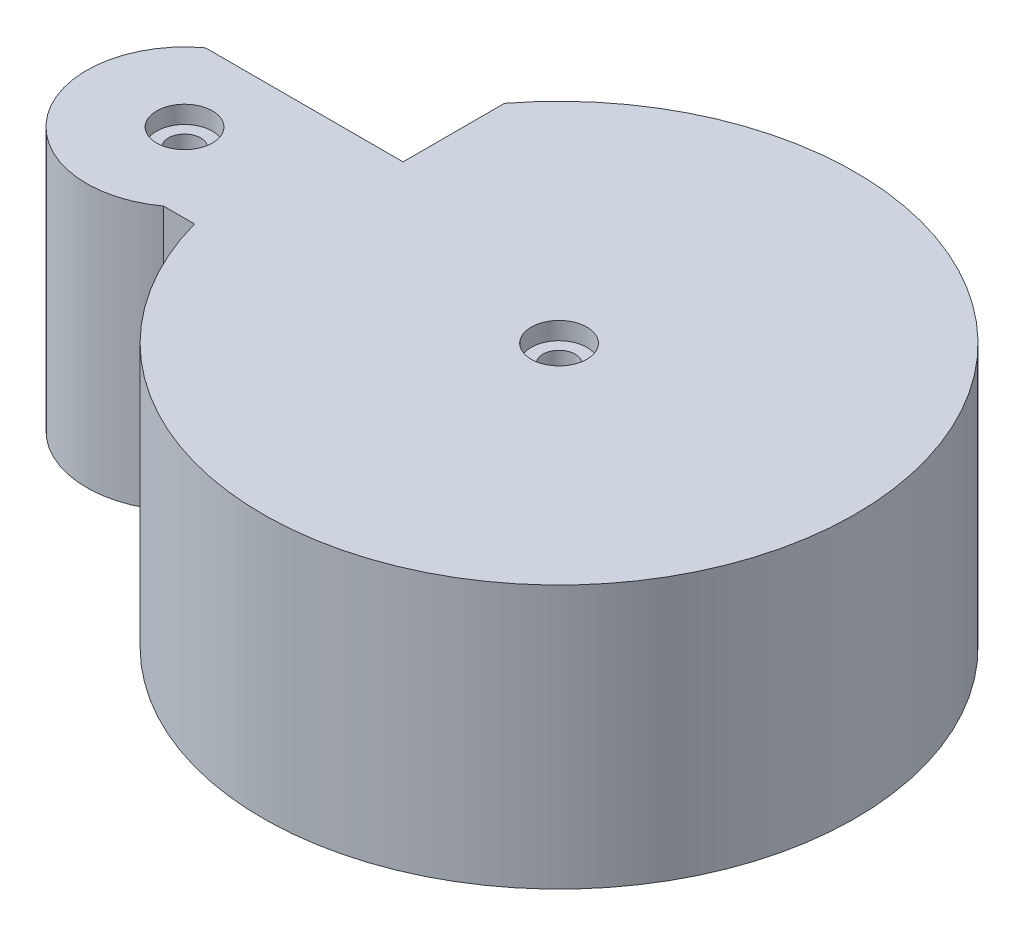
SolidWorks part; units mm, degrees
ref_plane "Plan de face" through (0, 0, 0) normal (0, 0, 1) x (1, 0, 0)
ref_plane "Plan de dessus" through (0, 0, 0) normal (0, 1, 0) x (1, 0, 0)
ref_plane "Plan de droite" through (0, 0, 0) normal (1, 0, 0) x (0, 0, -1)
sketch "Esquisse1" plane through (0, 0, 0) normal (0, 1, 0) x (1, 0, 0)
  line L0 (-85.33, 0) -> (0, 0) construction
  line L1 (-67.5, 22.9039) -> (-67.5, -22.4384) construction
  line L2 (-63, 20.67) -> (-63, -23.3426) construction
  line L3 (-98.5447, 18) -> (-53.5447, 18)
  line L4 (-53.5447, 18) -> (-53.5447, 41.1)
  line L5 (-65.0557, -18) -> (-72.1153, -18)
  circle A0 centre (0, 0) radius 67.5
  circle A1 centre (0, 0) radius 3.675
  circle A2 centre (-85.33, 0) radius 22.33
  circle A3 centre (-85.33, 0) radius 3.675
  point P10 (-63, 0)
  point P12 (-67.5, 0)
  point P17 (-66.4411, 11.9095)
  dimension "D1" = 135
  dimension "D2" = 7.35
  dimension "D3" = 4.5
  dimension "D4" = 44.66
  dimension "D5" = 45
  dimension "D6" = 18
  dimension "D7" = 18
extrude "Boss.-Extru.1" add sketch "Esquisse1" along normal blind 60 contours A0 A2 | A0 A2 | A2 A0 A1 | A2 A0 L3 | A2 L5 A0
sketch "Esquisse2" plane through (0, 0, 0) normal (0, -1, 0) x (1, 0, 0)
  line L1 (-96.58, 14.5) -> (-46.58, 14.5)
  line L2 (-96.58, 14.5) -> (-96.58, -14.5)
  line L3 (-96.58, -14.5) -> (-46.58, -14.5)
  line L4 (-46.58, 14.5) -> (-46.58, -14.5)
  point P4 (-96.58, 0)
  point P7 (-85.33, 0)
  dimension "D1" = 29
  dimension "D2" = 50
  dimension "D3" = 11.25
extrude "Enlèv. mat.-Extru.1" cut sketch "Esquisse2" against normal blind 40
hole_wizard "Dégagement M21" positions "Esquisse3D1" profile "Esquisse3" hole size "M2" standard "Ansi Metric"
sketch3d "Esquisse3D1"
  line L1 (-85.33, 60, 0) -> (-85.33, 60, -18) construction
  line L2 (-85.33, 60, 0) -> (-85.33, 40, 0) construction
  line L3 (-85.33, 60, 0) -> (-85.33, 0, 0) construction
  line L4 (-98.5447, 60, -18) -> (-53.5447, 60, -18) construction
  line L5 (-85.33, 60, -18) -> (-85.33, 3.9282, -18) construction
  point P0 (-57.33, 24.6, -18)
  point P2 (-81.33, 24.6, -18)
  point P4 (-81.33, 12.6, -18)
  point P6 (-57.33, 12.6, -18)
  dimension "D1" = 12
  dimension "D2" = 35.4
  dimension "D3" = 24
  dimension "D4" = 4
sketch "Esquisse3" plane through (-57.33, 24.6, -18) normal (1, 0, 0) x (0, 1, 0)
  line L0 (0, 0) -> (0, 3.5)
  line L1 (0, 3.5) -> (1.3, 3.5)
  line L2 (1.3, 3.5) -> (1.3, 0)
  line L5 (1.3, 0) -> (0, 0)
  line L11 (0, -6.35) -> (0, 107.95) construction
  dimension "Diamètre du perçage jusqu'au prochain" = 2.6
  dimension "Profondeur du perçage jusqu'au prochain" = 3.5
sketch "Esquisse4" plane through (0, 0, 0) normal (0, -1, 0) x (1, 0, 0)
  circle A0 centre (0, 0) radius 6.35
  dimension "D1" = 12.7
extrude "Enlèv. mat.-Extru.2" cut sketch "Esquisse4" against normal blind 4
sketch "Esquisse5" plane through (0, 60, 0) normal (0, 1, 0) x (1, 0, 0)
  circle A0 centre (0, 0) radius 6.35
  dimension "D1" = 12.7
extrude "Enlèv. mat.-Extru.3" cut sketch "Esquisse5" against normal blind 4
sketch "Esquisse6" plane through (0, 60, 0) normal (0, 1, 0) x (1, 0, 0)
  circle A0 centre (-85.33, 0) radius 6.35
  circle A1 centre (0, 0) radius 6.35 construction
extrude "Enlèv. mat.-Extru.4" cut sketch "Esquisse6" against normal blind 4
